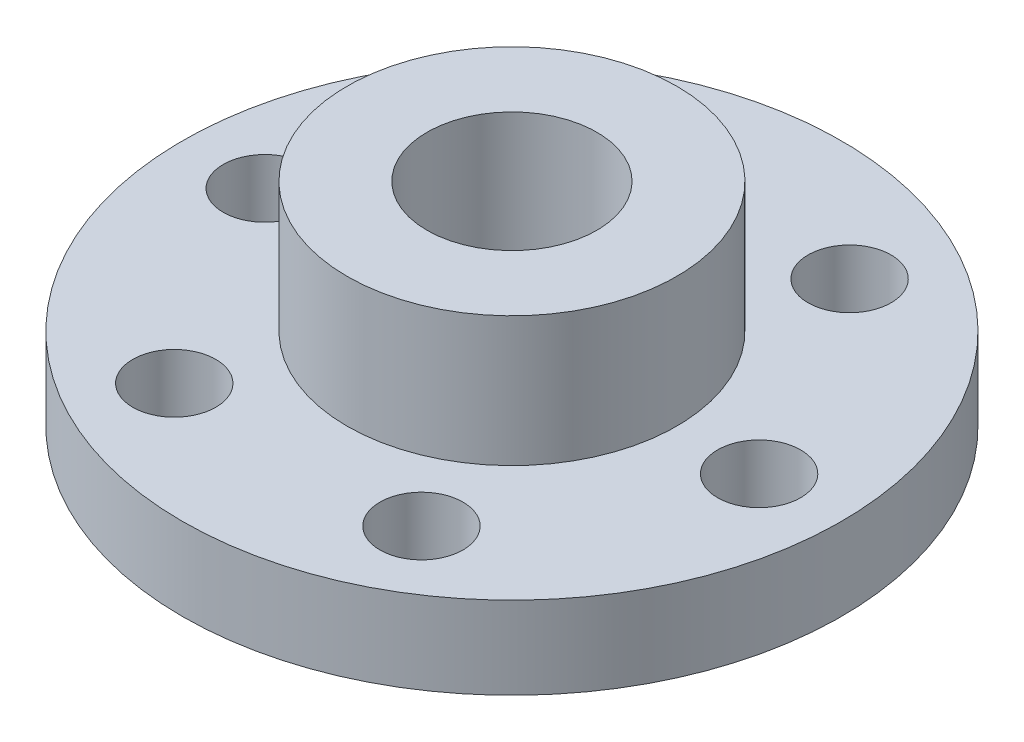
SolidWorks part; units mm, degrees
ref_plane "Front Plane" through (0, 0, 0) normal (0, 0, 1) x (1, 0, 0)
ref_plane "Top Plane" through (0, 0, 0) normal (0, 1, 0) x (1, 0, 0)
ref_plane "Right Plane" through (0, 0, 0) normal (1, 0, 0) x (0, 0, -1)
sketch "Sketch1" plane through (0, 0, 0) normal (0, 1, 0) x (1, 0, 0)
  line L0 (0, 0) -> (6.5484, 0) construction
  line L4 (0, 0) -> (-19.05, 0) construction
  circle A0 centre (0, 0) radius 4.826
  circle A1 centre (0, 0) radius 6.5484 construction
  arc A2 (3.9286, 10.8597) -> (3.9286, -10.8597) centre (0, 0) ccw construction
  circle A3 centre (0, 0) radius 25.4
  circle A5 centre (0, 0) radius 11.5484 construction
  circle A6 centre (-19.05, 0) radius 2.9766 construction
  dimension "D1" = 9.652
  dimension "D2" = 13.0969
  dimension "D3" = 23.0969
  dimension "D7" = 5.9531
  dimension "D5" = 50.8
  dimension "D4" = 19.05
extrude "main body" add sketch "Sketch1" along normal blind 6.35
sketch "Sketch2" plane through (0, 6.35, 0) normal (0, 1, 0) x (1, 0, 0)
  circle A0 centre (0, 0) radius 12.7
  circle A2 centre (0, 0) radius 6.5484
  dimension "D1" = 13.0969
  dimension "D2" = 25.4
extrude "tap boss" add sketch "Sketch2" along normal blind 10
hole_wizard "M6 Clearance Hole1" positions "Sketch3" profile "Sketch4" hole size "M6" standard "ANSI Metric" end condition through all
sketch "Sketch3" plane through (0, 6.35, 0) normal (0, 1, 0) x (1, 0, 0)
  point P0 (-19.05, 0)
  point P7 (-9.525, 16.4978)
  point P8 (9.525, 16.4978)
  point P9 (19.05, 0)
  point P10 (9.525, -16.4978)
  point P11 (-9.525, -16.4978)
  point P12 (0, 0)
  dimension "D1" = 6
sketch "Sketch4" plane through (-19.05, 6.35, 0) normal (1, 0, 0) x (0, 0, 1)
  line L0 (0, 0) -> (0, 6.35)
  line L1 (0, 6.35) -> (3.2, 6.35)
  line L2 (3.2, 6.35) -> (3.2, 0)
  line L5 (3.2, 0) -> (0, 0)
  line L11 (0, -6.35) -> (0, 107.95) construction
  dimension "Thru Hole Dia." = 6.4
  dimension "Thru Hole Depth" = 6.35
sketch "Sketch5" plane through (0, 0, 0) normal (0, -1, 0) x (1, 0, 0)
  line L0 (0, 0) -> (-25.4, 0) construction
  line L1 (-25.4, 0) -> (-25.4, 25.4) construction
  line L2 (-25.4, 25.4) -> (0, 25.4) construction
  line L3 (0, 25.4) -> (0, 0) construction
  circle A0 centre (0, 0) radius 25.4 construction
equation "\"z\"= 8\t\t\t\t'number of blades"
equation "\"de\"= 0.43in\t\t\t'entrance eye diameter"
equation "\"de_length\"= 4mm\t\t'entrance eye consistent length"
equation "\"d_exit\"= 0.18in \t\t'throat aka d1"
equation "\"d2\"= 2.1in \t\t\t'outer diameter of the impeller"
equation "\"b2\"= .2in\t\t\t'tip height from disc surface at d2; slightly higher than d_exit"
equation "\"b1\"= \"b2\" + (\"d2\"/2 - \"de\"/2)*tan(\"theta\") \t\t\t'tip height from disc surface at inlet eye"
equation "\"theta\"= 12\t\t\t'angle of blades from inner to outer "
equation "\"ae\"= 3.14*(\"de\"^2)/4\t\t'entrance eye area'"
equation "\"ce\"= 3.14*\"de\"\t\t'entrance eye circumference"
equation "\"av_ratio\"= .325\t\t'ratio of av/ae at N_s of 470, range is .275 to .375, .325 ideal. High ratio means bigger area means smaller blades"
equation "\"av\"= \"ae\"*\"av_ratio\"\t\t'area between just two blades"
equation "\"s_open\"= \"av\"/\"b1\"\t\t'width of open area"
equation "\"s\"=\"ce\" - \"z\"*\"s_open\""
equation "\"min blade thickness\"= .15in"
equation "\"bearing OD\"= 30mm"
equation "\"bearing ID\"= 10mm"
equation "\"bearing depth\"= 9mm"
equation "\"bearing outer race thickness\"= 1mm"
equation "\"bearing inner race thickness\"= 1mm"
equation "\"bearing bore\"= \"bearing depth\" + 1mm"
equation "\"lower seal OD\"= .917in\t\t'this is https://www.mcmaster.com/#9281k121/=174001b"
equation "\"lower seal ID\"= .375in"
equation "\"lower seal depth\"= .625in + .218in"
equation "\"lower seal bore\"= \"lower seal depth\" + 1mm"
equation "\"upper seal OD\"= 1.125in\t'this is https://www.mcmaster.com/#5154t33/=173zuau, needs to be visually inspected before machining!"
equation "\"upper seal ID\"= 0.625in"
equation "\"upper seal depth\"= .25in\t'aka height; these values need to be confirmed by inspection!! We may want to compress the height."
equation "\"upper seal bore\"= \"upper seal depth\" + 1mm"
equation "\"big o-ring thickness\"= .139in"
equation "\"big o-ring OD\"= 2.734in"
equation "\"big o-ring ID\"= 3.012in"
equation "\"big o-ring groove depth\"= \"big o-ring thickness\"*4/5"
equation "\"impeller center height\"= \"impeller base thickness\" + \"b1\"\t'impeller height at de"
equation "\"impeller outer height\"= \"impeller base thickness\" + \"b2\"\t'impeller height at de"
equation "\"impeller upper clearance\"= .5mm"
equation "\"impeller horizontal clearance\"= (\"d2\"*1.15 - \"d2\")/2 \t\t'clearance based on D2-D3 ratio for circular volute, ranges 1.15 to 1.2"
equation "\"impeller bottom clearance\"= .5mm"
equation "\"impeller base thickness\"= 2mm"
equation "\"impeller dowel diameter\"= 2mm"
equation "\"impeller bolt head diameter\"= \"m4 head bore diameter\""
equation "\"impeller bolt head depth\"= 4mm"
equation "\"impeller bolt stop depth\"= 3mm"
equation "\"impeller bolt bore\"= \"m4 clearance\""
equation "\"impeller shaft bore depth\"= 12mm"
equation "\"impeller shaft bore\"= 8mm"
equation "\"impeller boss depth\"= \"impeller shaft bore depth\"+\"impeller bolt stop depth\"+\"impeller bolt head depth\"-\"impeller base thickness\""
equation "\"impeller boss diameter\"= \"upper seal ID\""
equation "\"impeller dowel length\"= 2mm*2 + \"impeller shaft bore\""
equation "\"coupler motor shaft hole ID\"= 8mm"
equation "\"coupler OD\"= 17mm"
equation "\"coupler length\"= 25mm"
equation "\"motor OD\"= 64mm"
equation "\"motor shaft diameter\"= 8mm"
equation "\"motor shaft pride\"= 32mm"
equation "\"motor to bearing plate distance\"= \"motor shaft pride\" + 2mm +\"coupler length\"/2"
equation "\"square plate bolt bore\"= \"m8 clearance\""
equation "\"square plate bolt head diameter\"= 13.5mm"
equation "\"square plate bolt head depth\"= 8mm"
equation "\"square plate bolt pattern diameter\"= 3.5in"
equation "\"motor mount center bore\"= \"coupler OD\"+ 4mm"
equation "\"motor mount post radius\"= ( 3 * \"square plate bolt bore\" ) / 2"
equation "\"motor mount m4 screw hole diameter\"= 4mm"
equation "\"motor mount m4 head diameter\"= 7.25mm"
equation "\"motor mount m4 head depth\"= 4mm"
equation "\"motor mount m4 pattern diamater\"= 30mm"
equation "\"motor mount plate thickness\"= 8mm + \"motor mount m4 head depth\""
equation "\"bearing plate stop ID\"= \"bearing OD\" - 4mm"
equation "\"bearing plate stop depth\"= 3mm"
equation "\"bearing plate thickness\"= \"bearing bore\" + \"bearing plate stop depth\" + \"shaft bearing stop length\""
equation "\"lower seal plate lip depth\"= 2mm"
equation "\"lower seal plate lip ID\"= \"lower seal OD\" - 3mm"
equation "\"lower seal plate thickness\"= \"lower seal plate lip depth\" + \"lower seal bore\""
equation "\"shaft coupler section diameter\"= 8mm"
equation "\"shaft coupler section length\"= \"motor to bearing plate distance\" - \"motor shaft pride\" - 2mm"
equation "\"shaft bearing section diameter\"= \"bearing ID\""
equation "\"shaft bearing section length\"= \"bearing plate stop depth\" + \"bearing depth\""
equation "\"shaft bearing stop diameter\"= \"bearing ID\" + 4mm"
equation "\"shaft bearing stop length\"= 3mm"
equation "\"shaft lower seal section diameter\"= \"lower seal ID\""
equation "\"shaft lower seal section length\"= \"lower seal plate thickness\" + 1mm"
equation "\"shaft impeller section diameter\"= \"impeller shaft bore\""
equation "\"shaft impeller section length\"= \"upper seal plate thickness\" + \"upper seal plate riser\" + \"impeller bottom clearance\" + \"impeller base thickness\" - \"impeller bolt head depth\" - \"impeller bolt stop depth\""
equation "\"upper seal plate thickness\"= \"upper seal plate pressure hole diameter\"+10mm"
equation "\"upper seal plate lip ID\"= \"upper seal OD\" - 3mm"
equation "\"upper seal plate riser\"= 6.59mm \t\t'this number needs to be read from the housing file"
equation "\"upper seal plate pressure hole diameter\"= .125in\t'this is 1/8 drill "
equation "\"upper seal plate pressure tap diameter\"= .328125in \t'this is 21/64 drill for a 1/8 ANPT tap"
equation "\"upper seal plate pressure tap grip\"= 5mm\t\t'this is the area around the tap so it doesn't crack"
equation "\"upper seal plate pressure tap depth\"= 12mm"
equation "\"impeller cavity center height\"= \"impeller bottom clearance\" + \"impeller upper clearance\" + \"impeller center height\""
equation "\"impeller cavity diameter\"= 2 * \"impeller horizontal clearance\" + \"d2\" \t\t\t\t\t\t\t\t\t'called D3 analytically"
equation "\"impeller cavity outer height\"= \"impeller bottom clearance\" + \"impeller upper clearance\" + \"impeller base thickness\" + \"b2\" \t\t'this is height at impeller diameter d2, not at d3"
equation "\"impeller housing thickness\"= \"impeller housing exit threaded diameter\" + 2*\"impeller housing outlet grip\""
equation "\"impeller housing diameter\"= 4.5in"
equation "\"impeller housing bolt count\"= 8"
equation "\"impeller housing bolt diameter\"= \"m6 clearance\""
equation "\"impeller housing bolt pattern diameter\"= 3.5in"
equation "\"impeller housing threaded inlet diameter\"= 0.71875in \t'this is the 23/32 drill size for 1/2 NPT fitting https://www.mcmaster.com/#50715k269/=176pljy"
equation "\"impeller housing threaded inlet depth\"= .6in"
equation "\"impeller housing exit threaded diameter\"= 0.515625in \t\t'this is the 33/64 drill size for 9/16-18 fitting, expecting swagelok SS-8FK0-1-6STH fitting"
equation "\"impeller housing exit threaded depth\"= 10mm"
equation "\"impeller housing diffuser conical angle\"=10"
equation "\"impeller housing diffuser tangent angle\"=5"
equation "\"impeller housing diffuser final diameter\"= .38in\t\t'aka d2'"
equation "\"impeller housing outlet grip\"= 5mm"
equation "\"end mill size\"= 0.375in\t'for 3/8 endmill"
equation "\"m4 clearance\"= 0.171875in \t'this is 11/64 bit for 4.36mm"
equation "\"m4 tap\"= 0.125in\t\t'this is 1/8 bit for 3.17mm"
equation "\"m4 head bore diameter\"= 7.5mm"
equation "\"m4 head bore depth\"= 5mm\t'actual is ~4mm"
equation "\"m6 clearance\"= 0.234375in\t'this is 15/64 bit = 5.95mm, could use 6mm bit, B bit for 6.04mm or 1/4 bit for 6.35mm"
equation "\"m6 tap\"= 5mm\t\t\t'5mm is appropriate, could use 13/64 or #5,6,7"
equation "\"m6 head bore diameter\"= 11mm\t\t"
equation "\"m6 head bore depth\"= 7mm\t'actual is 6mm"
equation "\"m8 clearance\"= 0.3125in\t'this is 5/16in for 7.93mm, could use 8mm, O,P, or 21/64"
equation "\"m8 tap\"= 0.265625in\t\t'this is 17/64 for 6.746875mm"
equation "\"m8 head bore diameter\"= 14mm"
equation "\"m8 head bore depth\"= 9mm\t'actual is 8mm"
equation "\"D1@Sketch1\"=\"impeller housing diffuser final diameter\""
equation "\"D2@Sketch1\"=\"impeller housing exit threaded diameter\""
equation "\"D3@Sketch1\"=\"impeller housing exit threaded diameter\"+\"impeller housing outlet grip\"*2 "
equation "\"D7@Sketch1\"=\"m6 clearance\""
equation "\"D1@Sketch2\"=\"impeller housing exit threaded diameter\""
equation "\"D1@tap boss\"=10mm"
equation "\"diffuser cartridge OD\"=.75in"
equation "\"diffuser flange bolt pattern diameter\"= 1.4in"
equation "\"D4@Sketch1\"=.75in"
